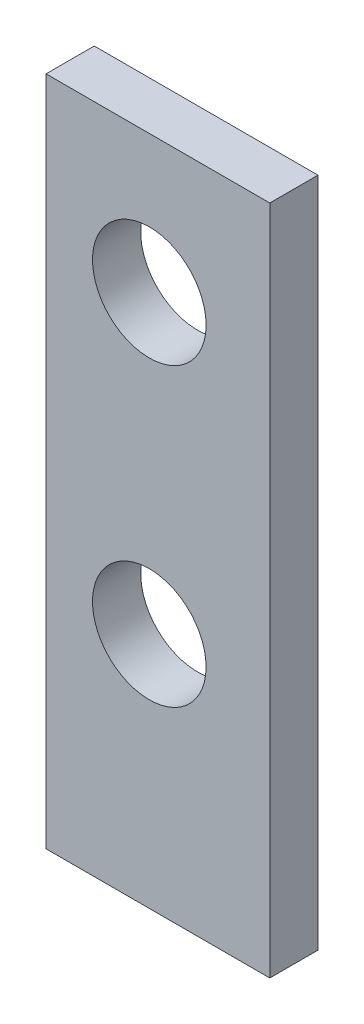
SolidWorks part; units mm, degrees
ref_plane "Front Plane" through (0, 0, 0) normal (0, 0, 1) x (1, 0, 0)
ref_plane "Top Plane" through (0, 0, 0) normal (0, 1, 0) x (1, 0, 0)
ref_plane "Right Plane" through (0, 0, 0) normal (1, 0, 0) x (0, 0, -1)
sketch "Sketch1" plane through (0, 0, 0) normal (0, 0, 1) x (1, 0, 0)
  line L1 (-33.7, -70.9) -> (-40.2, -70.9)
  line L2 (-33.7, -70.9) -> (-33.7, -51.4)
  line L3 (-33.7, -51.4) -> (-40.2, -51.4)
  line L4 (-40.2, -70.9) -> (-40.2, -51.4)
  circle A0 centre (-37.2, -55.4) radius 1.65 construction
  circle A1 centre (-37.2, -64) radius 1.65 construction
  circle A2 centre (-37.2, -64) radius 1.65
  circle A3 centre (-37.2, -55.4) radius 1.65
extrude "Boss-Extrude1" add sketch "Sketch1" along normal blind 1.4
